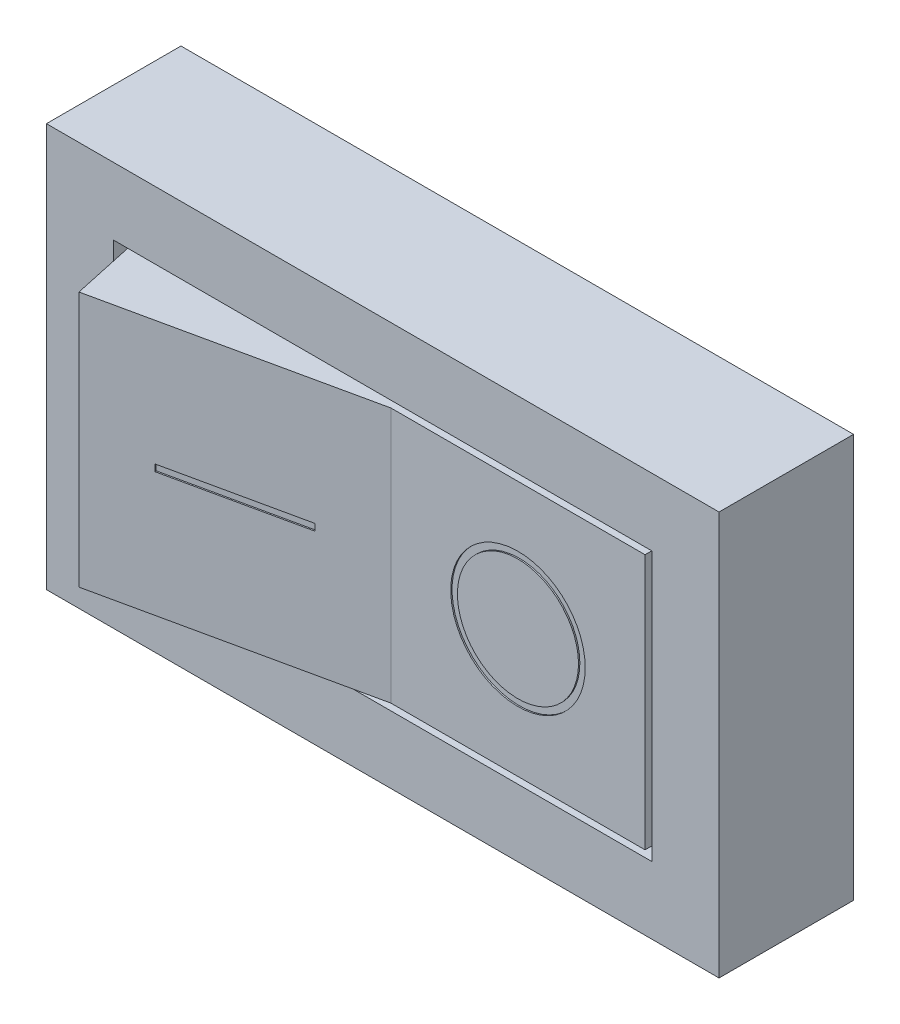
SolidWorks part; units mm, degrees
ref_plane "Front Plane" through (0, 0, 0) normal (0, 0, 1) x (1, 0, 0)
ref_plane "Top Plane" through (0, 0, 0) normal (0, 1, 0) x (1, 0, 0)
ref_plane "Right Plane" through (0, 0, 0) normal (1, 0, 0) x (0, 0, -1)
sketch "Sketch1" plane through (0, 0, 0) normal (0, 0, 1) x (1, 0, 0)
  line L1 (-19.3584, 10.9741) -> (20.6416, 10.9741)
  line L2 (-19.3584, 10.9741) -> (-19.3584, -9.0259)
  line L3 (-19.3584, -9.0259) -> (20.6416, -9.0259)
  line L4 (20.6416, 10.9741) -> (20.6416, -9.0259)
  dimension "D1" = 20
  dimension "D2" = 40
extrude "Extrude-Thin2" add sketch "Sketch1" along normal blind 10 thin thin type one direction wall 5
ref_plane "Plane1" through (0, 0, 5) normal (0, 0, 1) x (1, 0, 0)
sketch "Sketch2" plane through (0, 0, 5) normal (0, 0, 1) x (1, 0, 0)
  line L0 (20.6416, -9.0259) -> (20.6416, 10.9741) construction
  line L1 (0.1416, 10.4741) -> (20.1416, 10.4741)
  line L2 (0.1416, 10.4741) -> (0.1416, -8.5259)
  line L3 (0.1416, -8.5259) -> (20.1416, -8.5259)
  line L4 (20.1416, 10.4741) -> (20.1416, -8.5259)
  line L5 (20.6416, 10.9741) -> (-19.3584, 10.9741) construction
  line L8 (-19.3584, -9.0259) -> (20.6416, -9.0259) construction
  dimension "D1" = 0.5
  dimension "D2" = 0.5
  dimension "D3" = 0.5
  dimension "D4" = 20
extrude "Boss-Extrude1" add sketch "Sketch2" along normal blind 5 separate body
sketch "Sketch3" plane through (0, -8.5259, 0) normal (0, -1, 0) x (1, 0, 0)
  line L0 (0.1416, 4.8987) -> (1.2462, 10)
  line L1 (0.1416, 10) -> (20.1416, 10) construction
  line L2 (1.2462, 10) -> (0.1416, 10)
  line L3 (0.1416, 10) -> (0.1416, 4.8987)
  point P4 (0.1416, 4.3811)
  point P7 (0.1416, 4.8987)
  point P8 (3.9545, 10)
  point P9 (7.9206, 10)
  point P10 (3.1501, 10)
  point P11 (0, 0)
  point P12 (0, 0)
  point P13 (1.994, 10)
  point P14 (1.2462, 10)
extrude "Cut-Extrude1" cut sketch "Sketch3" against normal blind 19
sketch "Sketch6" plane through (-0.878, 0, 0.1901) normal (-0.9773, 0, 0.2116) x (0.2116, 0, 0.9773)
  line L1 (10.0372, 10.4741) -> (4.9213, 10.4741)
  line L2 (10.0372, 10.4741) -> (10.0372, -8.5259)
  line L3 (10.0372, -8.5259) -> (4.9213, -8.5259)
  line L4 (4.9213, 10.4741) -> (4.9213, -8.5259)
extrude "Boss-Extrude2" add sketch "Sketch6" along normal blind 19.5
sketch "Sketch7" plane through (0, 0, 10) normal (0, 0, 1) x (1, 0, 0)
  line L0 (20.1416, -8.5259) -> (20.1416, 10.4741) construction
  line L1 (20.1416, 10.4741) -> (1.2462, 10.4741) construction
  circle A1 centre (10.6939, 0.9741) radius 5
  circle A2 centre (10.6939, 0.9741) radius 4.5
  point P0 (20.1416, 0.9741)
  point P1 (10.6939, 10.4741)
  point P4 (10.6939, 0.9741)
  dimension "D1" = 0.5
  dimension "D2" = 10
extrude "Cut-Extrude3" cut sketch "Sketch7" against normal blind 0.1
sketch "Sketch9" plane through (2.1242, 0, 9.8099) normal (0.2116, 0, 0.9773) x (0.9773, 0, -0.2116)
  line L0 (-0.8984, 10.4741) -> (-0.8984, -8.5259) construction
  line L1 (-20.3984, 10.4741) -> (-0.8984, 10.4741) construction
  line L2 (-10.6484, 0.7241) -> (-10.6484, 1.2241) construction
  line L3 (-15.6484, 1.2241) -> (-5.6484, 1.2241)
  line L4 (-15.6484, 1.2241) -> (-15.6484, 0.7241)
  line L5 (-15.6484, 0.7241) -> (-5.6484, 0.7241)
  line L6 (-5.6484, 1.2241) -> (-5.6484, 0.7241)
  line L7 (-15.6484, 0.9741) -> (-5.6484, 0.9741) construction
  point P0 (-0.8984, 0.9741)
  point P1 (-10.6484, 10.4741)
  point P4 (-10.6484, 0.9741)
  point P7 (-47.179, 18.6199)
  point P12 (-10.6484, 0.7241)
  point P13 (-15.6484, 0.9741)
  point P14 (-10.6484, 0.9741)
  point P19 (-4.3148, 2.615)
  point P20 (-10.6484, 0.9741)
  dimension "D1" = 10
  dimension "D2" = 0.5
extrude "Cut-Extrude4" cut sketch "Sketch9" against normal blind 0.1
